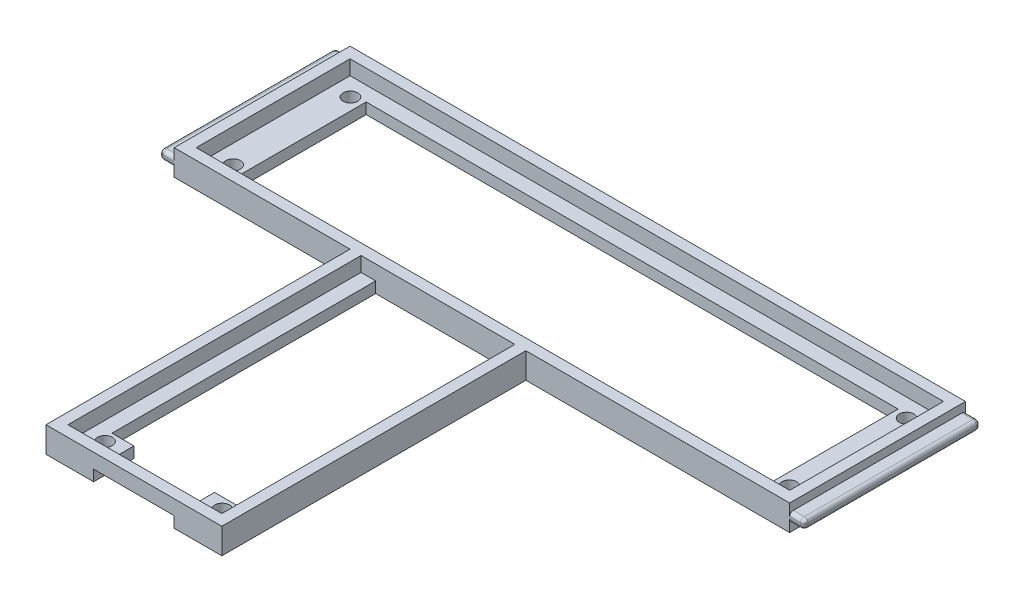
SolidWorks part; units mm, degrees
ref_plane "Front" through (0, 0, 0) normal (0, 0, 1) x (1, 0, 0)
ref_plane "Top" through (0, 0, 0) normal (0, 1, 0) x (1, 0, 0)
ref_plane "Right" through (0, 0, 0) normal (1, 0, 0) x (0, 0, -1)
sketch "Sketch2" plane through (0, 0, 0) normal (0, 1, 0) x (1, 0, 0)
  line L1 (-42, -12) -> (42, -12)
  line L2 (-42, -12) -> (-42, 12)
  line L3 (-42, 12) -> (42, 12)
  line L4 (42, -12) -> (42, 12)
  line L5 (-42, -12) -> (42, 12) construction
  line L6 (-42, 12) -> (42, -12) construction
  point P0 (0, 0)
  dimension "D1" = 84
  dimension "D2" = 24
extrude "Boss-Extrude1" add sketch "Sketch2" along normal blind 1.5
sketch "Sketch3" plane through (0, 1.5, 0) normal (0, 1, 0) x (1, 0, 0)
  line L9 (40.5, -10.5) -> (40.5, 10.5)
  line L10 (40.5, 10.5) -> (-40.5, 10.5)
  line L11 (-40.5, 10.5) -> (-40.5, -10.5)
  line L12 (-40.5, -10.5) -> (40.5, -10.5)
  line L13 (40.5, -10.5) -> (40.5, 10.5)
  line L14 (40.5, 10.5) -> (-40.5, 10.5)
  line L15 (-40.5, 10.5) -> (-40.5, -10.5)
  line L16 (-40.5, -10.5) -> (40.5, -10.5)
  line M5 (42, -12) -> (42, 12)
  line M6 (42, 12) -> (-42, 12)
  line M7 (-42, 12) -> (-42, -12)
  line M8 (-42, -12) -> (42, -12)
  dimension "D1" = 1.5
extrude "Boss-Extrude2" add sketch "Sketch3" along normal blind 2 contours L16 L15 L14 L13 M8 M5 M6 M7
sketch "Sketch4" plane through (0, 0, 0) normal (0, -1, 0) x (1, 0, 0)
  line L1 (-37.955, -8.005) -> (37.955, -8.005) construction
  line L2 (-37.955, -8.005) -> (-37.955, 8.005) construction
  line L3 (-37.955, 8.005) -> (37.955, 8.005) construction
  line L4 (37.955, -8.005) -> (37.955, 8.005) construction
  line L5 (-37.955, -8.005) -> (37.955, 8.005) construction
  line L6 (-37.955, 8.005) -> (37.955, -8.005) construction
  circle A0 centre (-37.955, 8.005) radius 1
  circle A1 centre (37.955, 8.005) radius 1
  circle A2 centre (37.955, -8.005) radius 1
  circle A3 centre (-37.955, -8.005) radius 1
  circle A4 centre (37.955, 8.005) radius 1.045 construction
  point P0 (0, 0)
  dimension "D1" = 2
extrude "Cut-Extrude1" cut sketch "Sketch4" against normal up to next
sketch "Sketch5" plane through (0, 1.5, 0) normal (0, 1, 0) x (1, 0, 0)
  line L0 (40.5, 10.5) -> (-40.5, 10.5) construction
  line L1 (-36.3, -8.5) -> (36.3, -8.5)
  line L2 (-36.3, -8.5) -> (-36.3, 8.5)
  line L3 (-36.3, 8.5) -> (36.3, 8.5)
  line L4 (36.3, -8.5) -> (36.3, 8.5)
  line L5 (-36.3, -8.5) -> (36.3, 8.5) construction
  line L6 (-36.3, 8.5) -> (36.3, -8.5) construction
  line L7 (40.5, -10.5) -> (40.5, 10.5) construction
  point P0 (0, 0)
  dimension "D1" = 2
  dimension "D2" = 4.2
extrude "Cut-Extrude2" cut sketch "Sketch5" against normal through all
sketch "Sketch6" plane through (0, 0, 0) normal (0, -1, 0) x (1, 0, 0)
  line L24 (-36.7426, 10.105) -> (-39.1674, 10.105)
  line L25 (-39.1674, 10.105) -> (-40.3799, 8.005)
  line L26 (-40.3799, 8.005) -> (-39.1674, 5.905)
  line L27 (-39.1674, 5.905) -> (-36.7426, 5.905)
  line L28 (-36.7426, 5.905) -> (-35.5301, 8.005)
  line L29 (-35.5301, 8.005) -> (-36.7426, 10.105)
  circle A4 centre (-37.955, 8.005) radius 2.4249 construction
  dimension "D1" = 4.2
extrude "Cut-Extrude3" [suppressed] cut sketch "Sketch6" against normal blind 2
sketch "Sketch7" plane through (0, 0, 0) normal (0, -1, 0) x (1, 0, 0)
  line L0 (-42, 12) -> (-49.5, 4.5)
  line L1 (-42, -12) -> (-49.5, -4.5)
  line L2 (-49.5, 4.5) -> (-49.5, -4.5)
  line L3 (-42, 12) -> (-42, -12)
  circle A1 centre (-46.5, 0) radius 1.5
  dimension "D2" = 3
  dimension "D1" = 9
  dimension "D3" = 3
extrude "Boss-Extrude3" [suppressed] add sketch "Sketch7" against normal blind 2
sketch "Sketch8" plane through (42, 0, 0) normal (1, 0, 0) x (0, 0, -1)
  line L0 (12, 3.5) -> (12, 0) construction
  line L1 (-12, 2.375) -> (12, 2.375)
  line L2 (-12, 2.375) -> (-12, 1.125)
  line L3 (-12, 1.125) -> (12, 1.125)
  line L4 (12, 2.375) -> (12, 1.125)
  line L5 (-12, 2.375) -> (12, 1.125) construction
  line L6 (-12, 1.125) -> (12, 2.375) construction
  line L7 (-12, 3.5) -> (-12, 0) construction
  point P0 (0, 1.75)
  point P15 (12, 1.75)
  point P16 (12, 1.75)
  dimension "D1" = 1.25
extrude "Boss-Extrude4" add sketch "Sketch8" along normal blind 2
fillet "Fillet1" radius 0.5 8 edges at (44, 1.125, 0) (44, 1.75, 12) (44, 2.375, 0) (44, 1.75, -12) (43, 2.375, -12) (43, 1.125, 12) (43, 1.125, -12) (43, 2.375, 12)
mirror "Mirror1" about plane through (0, 0, 0) normal (1, 0, 0) of "Fillet1", "Boss-Extrude4"
sketch "Sketch9" plane through (0, 0, 0) normal (0, 1, 0) x (1, 0, 0)
  line L0 (-42, -12) -> (42, -12) construction
  line L1 (6, -12) -> (-18, -12)
  line L2 (6, -12) -> (6, -53.5)
  line L3 (6, -53.5) -> (-18, -53.5)
  line L4 (-18, -12) -> (-18, -53.5)
  dimension "D1" = 24
  dimension "D2" = 41.5
  dimension "D3" = 6
extrude "Boss-Extrude5" add sketch "Sketch9" along normal up to surface (1.5 mm away) up to face at (0, 1.5, 0)
sketch "Sketch10" plane through (0, 1.5, 0) normal (0, 1, 0) x (1, 0, 0)
  line L5 (-16.5, -13.5) -> (-16.5, -12)
  line L6 (-42, -12) -> (42, -12) construction
  line L7 (4.5, -13.5) -> (4.5, -12)
  line L9 (4.5, -13.5) -> (-16.5, -13.5)
  line L10 (-16.5, -13.5) -> (-16.5, -52)
  line L11 (-16.5, -52) -> (4.5, -52)
  line L12 (4.5, -52) -> (4.5, -13.5)
  line L13 (4.5, -13.5) -> (-16.5, -13.5) construction
  line L14 (-16.5, -13.5) -> (-16.5, -52)
  line L15 (-16.5, -52) -> (4.5, -52)
  line L16 (4.5, -52) -> (4.5, -13.5)
  line M7 (6, -12) -> (-18, -12)
  line M8 (-18, -12) -> (-18, -53.5)
  line M9 (-18, -53.5) -> (6, -53.5)
  line M10 (6, -53.5) -> (6, -12)
  dimension "D1" = 1.5
extrude "Boss-Extrude6" add sketch "Sketch10" along normal up to surface (2 mm away) contours L16 L15 L14 L5 L7 M7 M8 M9 M10 up to face at (0, 3.5, 0)
sketch "Sketch11" plane through (0, 1.5, 0) normal (0, 1, 0) x (1, 0, 0)
  line L0 (-16.5, -52) -> (4.5, -52) construction
  line L1 (-16.5, -12) -> (-16.5, -52) construction
  line L2 (-14, -49.45) -> (2, -49.45) construction
  circle A0 centre (-14, -49.45) radius 1
  circle A1 centre (2, -49.45) radius 1
  point P8 (-6, -52)
  point P9 (-6, -49.45)
  dimension "D1" = 2
  dimension "D2" = 2.55
  dimension "D3" = 2.5
extrude "Cut-Extrude4" cut sketch "Sketch11" against normal through all
sketch "Sketch12" plane through (0, 1.5, 0) normal (0, 1, 0) x (1, 0, 0)
  line L0 (-16.5, -52) -> (4.5, -52) construction
  line L1 (-14.5, -48) -> (2.5, -48)
  line L2 (-14.5, -48) -> (-14.5, -12)
  line L3 (-14.5, -12) -> (2.5, -12)
  line L4 (2.5, -48) -> (2.5, -12)
  line L5 (-16.5, -12) -> (-16.5, -52) construction
  line L6 (4.5, -52) -> (4.5, -12) construction
  line L7 (-16.5, -12) -> (4.5, -12) construction
  point P10 (0.5, -45.5)
  point P11 (2.5, -12.4849)
  point P12 (2.5, -12)
  dimension "D1" = 4
  dimension "D2" = 2
  dimension "D3" = 2
extrude "Cut-Extrude5" cut sketch "Sketch12" against normal through all
sketch "Sketch13" plane through (0, 0, 0) normal (0, -1, 0) x (1, 0, 0)
  line L0 (-14.5, 48) -> (2.5, 48) construction
  line L1 (-11.5, 48) -> (-0.5, 48)
  line L2 (-11.5, 48) -> (-11.5, 53.5)
  line L3 (-11.5, 53.5) -> (-0.5, 53.5)
  line L4 (-0.5, 48) -> (-0.5, 53.5)
  line L5 (-18, 53.5) -> (6, 53.5) construction
  line L6 (2.5, 12) -> (-14.5, 12) construction
  point P8 (-6, 48)
  point P11 (-6, 12)
  point P12 (-0.1641, 47.5)
  dimension "D1" = 11
extrude "Cut-Extrude6" cut sketch "Sketch13" against normal up to surface (1.5 mm away) up to face at (-14, 1.5, 50.45)
